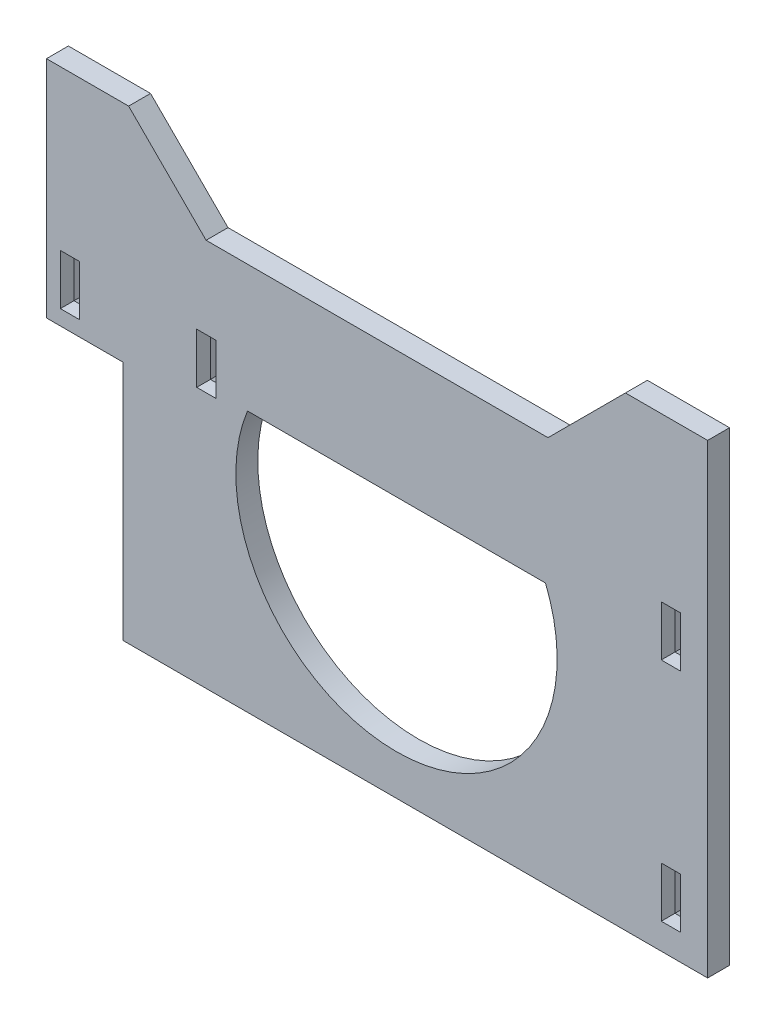
SolidWorks part; units mm, degrees
ref_plane "Front Plane" through (0, 0, 0) normal (0, 0, 1) x (1, 0, 0)
ref_plane "Top Plane" through (0, 0, 0) normal (0, 1, 0) x (1, 0, 0)
ref_plane "Right Plane" through (0, 0, 0) normal (1, 0, 0) x (0, 0, -1)
sketch "Sketch1" plane through (0, 0, 0) normal (0, 0, 1) x (1, 0, 0)
  line L0 (-31.5106, 17.6478) -> (22.8986, 17.6478)
  line L6 (-40.7725, 25.95) -> (-37.2425, 25.95)
  line L9 (-40.7725, 25.95) -> (-40.7725, 16.75)
  line L12 (-40.7725, 16.75) -> (-37.2425, 16.75)
  line L15 (-37.2425, 25.95) -> (-37.2425, 16.75)
  line L51 (52.4925, 30) -> (52.4925, -30)
  line L54 (44.0275, 25.25) -> (47.5575, 25.25)
  line L55 (44.0275, 25.25) -> (44.0275, 16.05)
  line L56 (44.0275, 16.05) -> (47.5575, 16.05)
  line L57 (47.5575, 25.25) -> (47.5575, 16.05)
  line L58 (47.565, -16.05) -> (44.035, -16.05)
  line L59 (47.565, -16.05) -> (47.565, -25.25)
  line L60 (47.565, -25.25) -> (44.035, -25.25)
  line L61 (44.035, -16.05) -> (44.035, -25.25)
  line L65 (-65.6725, 25.95) -> (-62.1425, 25.95)
  line L66 (-65.6725, 25.95) -> (-65.6725, 16.75)
  line L67 (-65.6725, 16.75) -> (-62.1425, 16.75)
  line L68 (-62.1425, 25.95) -> (-62.1425, 16.75)
  line L76 (52.4925, 30) -> (-68.2075, 30)
  line L81 (-39.0075, 25.95) -> (-39.0075, 16.75) construction
  line L82 (-37.2425, 21.35) -> (-40.7725, 21.35) construction
  line L83 (-63.9075, 25.95) -> (-63.9075, 16.75) construction
  line L84 (-62.1425, 21.35) -> (-65.6725, 21.35) construction
  line L85 (47.5575, 20.65) -> (44.0275, 20.65) construction
  line L86 (45.7925, 25.25) -> (45.7925, 16.05) construction
  line L87 (45.8, -16.05) -> (45.8, -25.25) construction
  line L88 (47.565, -20.65) -> (44.035, -20.65) construction
  line L89 (-54.2075, -30) -> (-54.2075, 14)
  line L90 (-54.2075, 14) -> (-68.2075, 14)
  line L91 (-68.2075, 14) -> (-68.2075, 30)
  line L92 (-54.2075, -30) -> (52.4925, -30)
  arc A12 (-31.5106, 17.6478) -> (22.8986, 17.6478) centre (-4.306, 6.6977) ccw
  point P0 (-0.0075, 0)
  point P14 (52.4925, 0)
  point P25 (-7.8575, 30)
  dimension "D3" = 3.53
  dimension "D4" = 9.2
  dimension "D6" = 60
  dimension "D5" = 24.9
  dimension "D7" = 53.65
  dimension "D2" = 31.15
  dimension "D10" = 20.65
  dimension "D11" = 20.65
  dimension "D8" = 120.7
  dimension "D9" = 14
  dimension "D12" = 44
extrude "Boss-Extrude1" add sketch "Sketch1" along normal blind 4
sketch "Sketch2" plane through (0, 0, 0) normal (0, 0, 1) x (1, 0, 0)
  line L0 (-68.2075, 30) -> (52.4925, 30)
  line L4 (23.3504, 40.8579) -> (-39.0654, 40.8579)
  line L5 (-39.0654, 40.8579) -> (-53.2075, 55)
  line L6 (-53.2075, 55) -> (-68.2075, 55)
  line L7 (-68.2075, 55) -> (-68.2075, 30)
  line L8 (23.3504, 40.8579) -> (37.4925, 55)
  line L9 (37.4925, 55) -> (52.4925, 55)
  line L10 (52.4925, 55) -> (52.4925, 30)
  line L12 (-68.2075, 30) -> (-68.2075, 14) construction
  dimension "D1" = 25
  dimension "D2" = 20
  dimension "D3" = 15
  dimension "D4" = 135
extrude "Boss-Extrude2" add sketch "Sketch2" along normal blind 4
sketch "Sketch3" plane through (0, 0, 0) normal (0, 0, -1) x (-1, 0, 0)
  line L0 (-45.7925, 25.25) -> (-45.7925, 16.05) construction
  line L1 (-47.5575, 25.25) -> (-44.0275, 25.25) construction
  line L2 (-44.0275, 16.05) -> (-47.5575, 16.05) construction
  line L3 (-47.5575, 20.65) -> (-44.0275, 20.65) construction
  line L4 (-47.5575, 16.05) -> (-47.5575, 25.25) construction
  line L5 (-44.0275, 25.25) -> (-44.0275, 16.05) construction
  line L6 (-45.8, -16.05) -> (-45.8, -25.25) construction
  line L7 (-47.565, -16.05) -> (-44.035, -16.05) construction
  line L8 (-44.035, -25.25) -> (-47.565, -25.25) construction
  line L9 (-47.565, -20.65) -> (-44.035, -20.65) construction
  line L10 (-47.565, -25.25) -> (-47.565, -16.05) construction
  line L11 (-44.035, -16.05) -> (-44.035, -25.25) construction
  line L12 (39.0075, 25.95) -> (39.0075, 16.75) construction
  line L13 (37.2425, 25.95) -> (40.7725, 25.95) construction
  line L14 (40.7725, 16.75) -> (37.2425, 16.75) construction
  line L15 (37.2425, 21.35) -> (40.7725, 21.35) construction
  line L16 (37.2425, 16.75) -> (37.2425, 25.95) construction
  line L17 (40.7725, 25.95) -> (40.7725, 16.75) construction
  line L18 (63.9075, 25.95) -> (63.9075, 16.75) construction
  line L19 (62.1425, 25.95) -> (65.6725, 25.95) construction
  line L20 (65.6725, 16.75) -> (62.1425, 16.75) construction
  line L21 (62.1425, 21.35) -> (65.6725, 21.35) construction
  line L22 (62.1425, 16.75) -> (62.1425, 25.95) construction
  line L23 (65.6725, 25.95) -> (65.6725, 16.75) construction
chamfer "Chamfer1" distance 1.5 distance2 0.5 16 edges at (45.8, -25.25, 0) (44.035, -20.65, 0) (45.8, -16.05, 0) (47.565, -20.65, 0) (-63.9075, 25.95, 0) (-62.1425, 21.35, 0) (-63.9075, 16.75, 0) (-65.6725, 21.35, 0) (-39.0075, 25.95, 0) (-37.2425, 21.35, 0) (-39.0075, 16.75, 0) (-40.7725, 21.35, 0) (45.7925, 25.25, 0) (47.5575, 20.65, 0) (45.7925, 16.05, 0) (44.0275, 20.65, 0)
equation "\"pin_hole_width\"=3.53"
equation "\"D3@Sketch1\"=\"pin_hole_width\""
equation "\"pin_hole_height\"=9.2"
equation "\"D4@Sketch1\"=\"pin_hole_height\""
equation "\"distancer\"=24.9"
equation "\"D5@Sketch1\"=\"distancer\""
